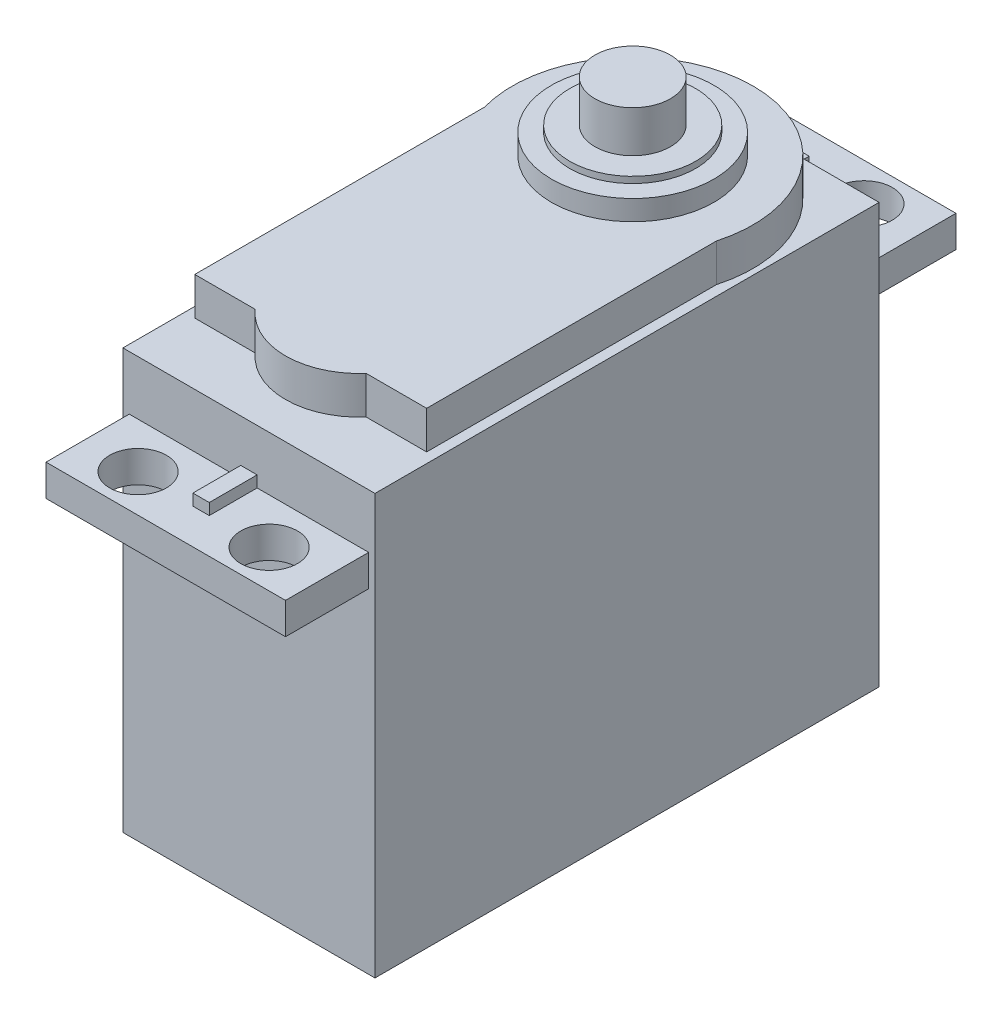
SolidWorks part; units mm, degrees
ref_plane "Front Plane" through (0, 0, 0) normal (0, 0, 1) x (1, 0, 0)
ref_plane "Top Plane" through (0, 0, 0) normal (0, 1, 0) x (1, 0, 0)
ref_plane "Right Plane" through (0, 0, 0) normal (1, 0, 0) x (0, 0, -1)
sketch "Sketch1" plane through (0, 0, 0) normal (0, 1, 0) x (1, 0, 0)
  line L1 (0, 0) -> (20, 0)
  line L2 (0, 0) -> (0, 40)
  line L3 (0, 40) -> (20, 40)
  line L4 (20, 0) -> (20, 40)
  dimension "D1" = 20
  dimension "D2" = 40
extrude "Boss-Extrude1" add sketch "Sketch1" along normal blind 33.3
sketch "Sketch2" plane through (0, 0, 0) normal (0, 0, 1) x (1, 0, 0)
  line L1 (0.5, 29) -> (19.5, 29)
  line L2 (0.5, 29) -> (0.5, 26.5)
  line L3 (0.5, 26.5) -> (19.5, 26.5)
  line L4 (19.5, 29) -> (19.5, 26.5)
  line L5 (0, 33.3) -> (0, 0) construction
  line L6 (0, 33.3) -> (20, 33.3) construction
  dimension "D1" = 19
  dimension "D2" = 2.5
  dimension "D3" = 0.5
  dimension "D4" = 4.3
extrude "Boss-Extrude2" add sketch "Sketch2" along normal blind 6.6
sketch "Sketch3" plane through (0, 0, -40) normal (0, 0, -1) x (-1, 0, 0)
  line L0 (-20, 33.3) -> (0, 33.3) construction
  line L1 (-19.5, 29) -> (-0.5, 29)
  line L2 (-19.5, 29) -> (-19.5, 26.5)
  line L3 (-19.5, 26.5) -> (-0.5, 26.5)
  line L4 (-0.5, 29) -> (-0.5, 26.5)
  line L7 (-20, 33.3) -> (-20, 0) construction
  dimension "D2" = 2.5
  dimension "D1" = 4.3
  dimension "D3" = 19
  dimension "D4" = 0.5
extrude "Boss-Extrude3" add sketch "Sketch3" along normal blind 6.6
sketch "Sketch4" plane through (0, 33.3, 0) normal (0, 1, 0) x (1, 0, 0)
  line L0 (20, 40) -> (0, 40) construction
  line L1 (0, 40) -> (0, 0) construction
  circle A0 centre (10, 30.45) radius 9.55
  dimension "D1" = 19.1
  dimension "D2" = 9.55
  dimension "D3" = 10
extrude "Boss-Extrude4" add sketch "Sketch4" along normal blind 3
sketch "Sketch12" plane through (0, 33.3, 0) normal (0, 1, 0) x (1, 0, 0)
  line L0 (0, 0) -> (20, 0) construction
  line L1 (19.2, 4.9) -> (0.8, 4.9)
  line L2 (19.2, 4.9) -> (19.2, 30.9)
  line L3 (19.2, 30.9) -> (0.8, 30.9)
  line L4 (0.8, 4.9) -> (0.8, 30.9)
  line L5 (0, 40) -> (0, 0) construction
  dimension "D1" = 18.4
  dimension "D2" = 26
  dimension "D3" = 4.9
  dimension "D4" = 0.8
extrude "Boss-Extrude10" add sketch "Sketch12" along normal blind 3
sketch "Sketch11" plane through (0, 0, -40) normal (0, 0, -1) x (-1, 0, 0)
  line L0 (-20, 0) -> (0, 0) construction
  line L5 (0, 33.3) -> (0, 0) construction
  circle A0 centre (-11.2, 2.4) radius 0.5
  dimension "D1" = 1
  dimension "D2" = 2.4
  dimension "D3" = 11.2
extrude "Boss-Extrude9" add sketch "Sketch11" along normal blind 3
pattern_linear "LPattern2" count 3 spacing 1.01 along (-1, 0, 0) of "Boss-Extrude9"
sketch "Sketch13" plane through (0, 36.3, 0) normal (0, 1, 0) x (1, 0, 0)
  circle A0 centre (10, 30.45) radius 6.45
  dimension "D1" = 12.9
extrude "Boss-Extrude11" add sketch "Sketch13" along normal blind 1.6
sketch "Sketch14" plane through (0, 37.9, 0) normal (0, 1, 0) x (1, 0, 0)
  circle A0 centre (10, 30.45) radius 5
  dimension "D1" = 10
extrude "Boss-Extrude12" add sketch "Sketch14" along normal blind 0.5
sketch "Sketch15" plane through (0, 38.4, 0) normal (0, 1, 0) x (1, 0, 0)
  circle A0 centre (10, 30.45) radius 3
  dimension "D1" = 6
extrude "Boss-Extrude13" add sketch "Sketch15" along normal blind 3.3
sketch "Sketch16" plane through (0, 33.3, 0) normal (0, 1, 0) x (1, 0, 0)
  line L0 (10, 4.9) -> (10, 2.9) construction
  line L1 (0.8, 4.9) -> (19.2, 4.9) construction
  line L2 (14.4, 4.9) -> (5.6, 4.9)
  arc A0 (5.6, 4.9) -> (14.4, 4.9) centre (10, 8.74) ccw
  dimension "D1" = 2
  dimension "D2" = 4.8
  dimension "D3" = 4.8
extrude "Boss-Extrude14" add sketch "Sketch16" along normal blind 3
sketch "Sketch17" plane through (0, 29, 0) normal (0, 1, 0) x (1, 0, 0)
  line L0 (19.5, 0) -> (0.5, 0) construction
  line L1 (10.65, 0) -> (9.35, 0)
  line L2 (10.65, 0) -> (10.65, -3.8)
  line L3 (10.65, -3.8) -> (9.35, -3.8)
  line L4 (9.35, 0) -> (9.35, -3.8)
  line L5 (19.5, -6.6) -> (19.5, 0) construction
  dimension "D1" = 1.3
  dimension "D2" = 3.8
  dimension "D3" = 8.85
extrude "Boss-Extrude15" add sketch "Sketch17" along normal blind 0.9
sketch "Sketch18" plane through (0, 29, 0) normal (0, 1, 0) x (1, 0, 0)
  line L0 (0.5, 40) -> (19.5, 40) construction
  line L1 (9.35, 40) -> (10.65, 40)
  line L2 (9.35, 40) -> (9.35, 43.8)
  line L3 (9.35, 43.8) -> (10.65, 43.8)
  line L4 (10.65, 40) -> (10.65, 43.8)
  line L5 (0.5, 46.6) -> (0.5, 40) construction
  dimension "D1" = 1.3
  dimension "D2" = 3.8
  dimension "D3" = 8.85
extrude "Boss-Extrude16" add sketch "Sketch18" along normal blind 0.9
hole_wizard "M4 Clearance Hole1" positions "Sketch19" profile "Sketch20" hole size "M4" standard "ANSI Metric"
sketch "Sketch19" plane through (0, 29, 0) normal (0, 1, 0) x (1, 0, 0)
  line L0 (19.5, -6.6) -> (19.5, 0) construction
  line L1 (0.5, -6.6) -> (0.5, 0) construction
  line L2 (0.5, 46.6) -> (0.5, 40) construction
  line L3 (19.5, 46.6) -> (19.5, 40) construction
  line L4 (0.5, 40) -> (9.35, 40) construction
  line L5 (10.65, 40) -> (19.5, 40) construction
  line L6 (9.35, 0) -> (0.5, 0) construction
  line L7 (19.5, 0) -> (10.65, 0) construction
  point P0 (4.8, 43.6)
  point P2 (15.2, 43.6)
  point P4 (4.8, -3.6)
  point P6 (15.2, -3.6)
  dimension "D1" = 4.3
  dimension "D2" = 4.3
  dimension "D3" = 4.3
  dimension "D4" = 4.3
  dimension "D5" = 3.6
  dimension "D6" = 3.6
  dimension "D7" = 3.6
  dimension "D8" = 3.6
sketch "Sketch20" plane through (4.8, 29, -43.6) normal (1, 0, 0) x (0, 0, 1)
  line L0 (0, 0) -> (0, 4.3519)
  line L1 (0, 4.3519) -> (2.25, 3)
  line L2 (2.25, 3) -> (2.25, 0)
  line L5 (2.25, 0) -> (0, 0)
  line L10 (0, 4.3519) -> (-2.25, 3) construction
  line L11 (0, -6.35) -> (0, 107.95) construction
  dimension "Hole Dia." = 4.5
  dimension "Hole Depth" = 3
  dimension "Drill Angle" = 118
equation "\"laser\"= 0.18'Laser Kerf"
equation "\"D3@Sketch2\"=(\"D1@Sketch1\"-\"D1@Sketch2\")/2"
equation "\"D4@Sketch3\"=\"D3@Sketch2\""
equation "\"D2@Sketch4\"=\"D1@Sketch4\"/2"
equation "\"D3@Sketch4\"=\"D1@Sketch1\"/2"
equation "\"D3@Sketch17\"=(\"D1@Sketch2\"-\"D1@Sketch17\")/2"
equation "\"D1@Sketch18\"=\"D1@Sketch17\""
equation "\"D2@Sketch18\"=\"D2@Sketch17\""
equation "\"D3@Sketch18\"=\"D3@Sketch17\""
